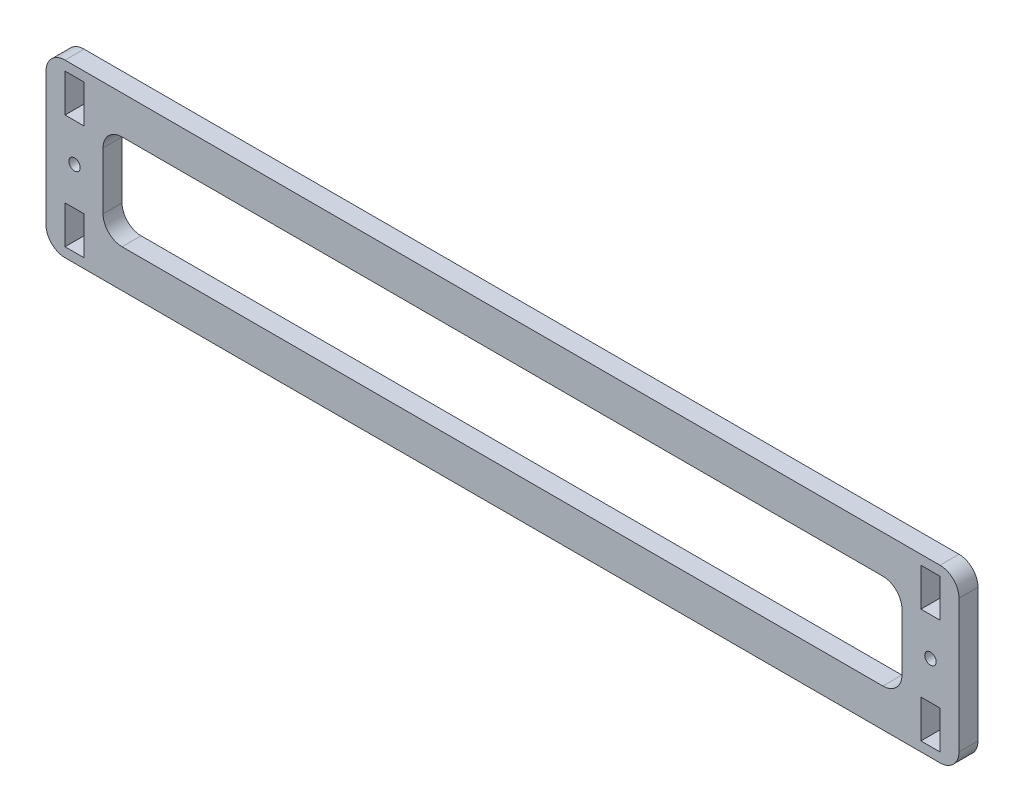
SolidWorks part; units mm, degrees
ref_plane "Front Plane" through (0, 0, 0) normal (0, 0, 1) x (1, 0, 0)
ref_plane "Top Plane" through (0, 0, 0) normal (0, 1, 0) x (1, 0, 0)
ref_plane "Right Plane" through (0, 0, 0) normal (1, 0, 0) x (0, 0, -1)
sketch "Sketch1" plane through (0, 0, 0) normal (0, 0, 1) x (1, 0, 0)
  line L0 (-90.218, 10) -> (299.3045, 10) construction
  line L1 (-85.8133, 22.5) -> (154.1867, 22.5)
  line L2 (-85.8133, 22.5) -> (-85.8133, -22.5)
  line L3 (-85.8133, -22.5) -> (154.1867, -22.5)
  line L4 (154.1867, 22.5) -> (154.1867, -22.5)
  line L5 (-80.8133, -10) -> (-75.8133, -10)
  line L6 (-91.3268, 0) -> (299.3045, 0) construction
  line L7 (-80.8133, 20) -> (-75.8133, 20)
  line L8 (-80.8133, 20) -> (-80.8133, 10)
  line L9 (-80.8133, 10) -> (-75.8133, 10)
  line L10 (-75.8133, 20) -> (-75.8133, 10)
  line L11 (-75.8133, -20) -> (-75.8133, -10)
  line L12 (-80.8133, -20) -> (-75.8133, -20)
  line L13 (-80.8133, -20) -> (-80.8133, -10)
  line L14 (34.1867, 30.0157) -> (34.1867, -45.8134) construction
  line L15 (-78.3133, 24.0051) -> (-78.3133, -32.23) construction
  line L16 (149.1867, -20) -> (149.1867, -10)
  line L17 (149.1867, -20) -> (144.1867, -20)
  line L18 (144.1867, -20) -> (144.1867, -10)
  line L19 (149.1867, -10) -> (144.1867, -10)
  line L20 (149.1867, 10) -> (144.1867, 10)
  line L21 (144.1867, 20) -> (144.1867, 10)
  line L22 (149.1867, 20) -> (144.1867, 20)
  line L23 (149.1867, 20) -> (149.1867, 10)
  circle A31 centre (-78.3133, 0) radius 1.5
  circle A32 centre (146.6867, 0) radius 1.5
  point P6 (34.1867, -22.5)
  point P13 (-85.8133, 0)
  point P82 (-78.3133, 20)
  dimension "D1" = 45
  dimension "D2" = 240
  dimension "D3" = 12.5
  dimension "D4" = 10
  dimension "D7" = 5
  dimension "D8" = 5
extrude "Boss-Extrude1" add sketch "Sketch1" along normal blind 5
sketch "Esquisse1" plane through (0, 0, 5) normal (0, 0, 1) x (1, 0, 0)
  line L0 (154.1867, 22.5) -> (-85.8133, 22.5) construction
  line L1 (-70.8133, 12.5) -> (139.1867, 12.5)
  line L2 (-70.8133, 12.5) -> (-70.8133, -12.5)
  line L3 (-70.8133, -12.5) -> (139.1867, -12.5)
  line L4 (139.1867, 12.5) -> (139.1867, -12.5)
  line L5 (-85.8133, -22.5) -> (154.1867, -22.5) construction
  line L6 (-75.8133, 10) -> (-75.8133, 20) construction
  line L7 (144.1867, 20) -> (144.1867, 10) construction
  dimension "D1" = 10
  dimension "D2" = 10
  dimension "D3" = 5
  dimension "D4" = 5
extrude "Enlèv. mat.-Extru.1" cut sketch "Esquisse1" against normal blind 10
fillet "Congé1" radius 5 8 edges at (139.1867, -12.5, 2.5) (-70.8133, -12.5, 2.5) (-70.8133, 12.5, 2.5) (139.1867, 12.5, 2.5) (-85.8133, -22.5, 2.5) (154.1867, 22.5, 2.5) (154.1867, -22.5, 2.5) (-85.8133, 22.5, 2.5)
